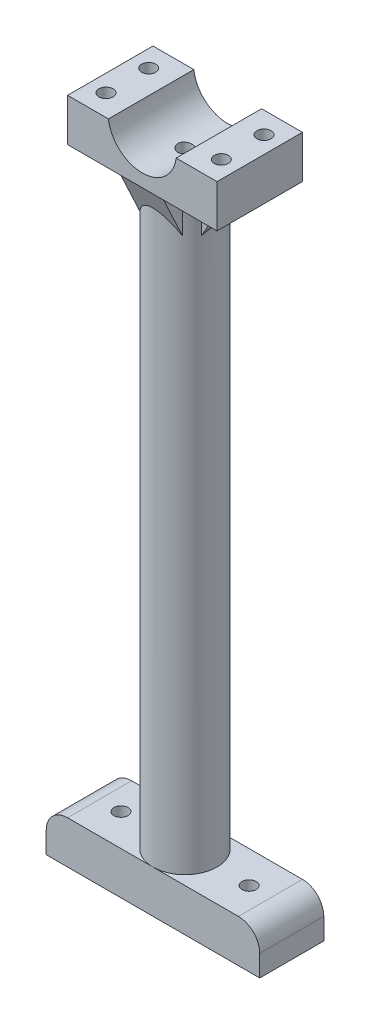
SolidWorks part; units mm, degrees
ref_plane "前视基准面" through (0, 0, 0) normal (0, 0, 1) x (1, 0, 0)
ref_plane "上视基准面" through (0, 0, 0) normal (0, 1, 0) x (1, 0, 0)
ref_plane "右视基准面" through (0, 0, 0) normal (1, 0, 0) x (0, 0, -1)
sketch "草图1" plane through (0, 0, 0) normal (0, 1, 0) x (1, 0, 0)
  line L1 (-25, -7.5) -> (25, -7.5)
  line L2 (-25, -7.5) -> (-25, 7.5)
  line L3 (-25, 7.5) -> (25, 7.5)
  line L4 (25, -7.5) -> (25, 7.5)
  line L5 (-25, -7.5) -> (25, 7.5) construction
  line L6 (-25, 7.5) -> (25, -7.5) construction
  point P0 (0, 0)
  dimension "D1" = 50
  dimension "D2" = 15
extrude "凸台-拉伸1" add sketch "草图1" along normal blind 10
sketch "草图2" plane through (0, 10, 0) normal (0, 1, 0) x (1, 0, 0)
  circle A0 centre (0, 0) radius 7.5
  dimension "D1" = 15
extrude "凸台-拉伸2" add sketch "草图2" along normal blind 150
sketch "草图3" plane through (0, 0, 0) normal (0, 0, 1) x (1, 0, 0)
  line L0 (-7.5, 160) -> (-7.5, 10) construction
  line L5 (0, 160) -> (0, 149)
  line L6 (-7.5, 160) -> (-7.5, 10) construction
  line L7 (7.5, 160) -> (-7.5, 160) construction
  line L8 (-17.5, 156) -> (17.5, 156)
  line L9 (-17.5, 156) -> (-17.5, 159)
  line L10 (-17.5, 159) -> (17.5, 159)
  line L11 (17.5, 156) -> (17.5, 159)
  line L12 (-17.5, 156) -> (17.5, 159) construction
  line L13 (-17.5, 159) -> (17.5, 156) construction
  line L14 (-17.5, 156) -> (-17.5, 149)
  line L15 (-17.5, 149) -> (17.5, 149)
  line L16 (17.5, 149) -> (17.5, 156)
  circle A0 centre (0, 160) radius 8
  circle A1 centre (0, 160) radius 11
  point P3 (0, 157.5)
  dimension "D1" = 16
  dimension "D2" = 22
  dimension "D3" = 10
  dimension "D4" = 1
  dimension "D5" = 7.5
  dimension "D6" = 0
  dimension "D7" = 3
extrude "凸台-拉伸3" add sketch "草图3" along normal blind 10 and the other way blind 10 contours A1 L10 L9 L8 | L10 A1 L8 A0 | L8 A1 L5 A0 | L5 A1 L8 A0 | L8 A1 L10 A0 | A1 L8 L11 L10 | A1 L8 L14 L15 | A1 L15 L16 L8
sketch "草图4" plane through (0, 0, 0) normal (0, 0, 1) x (1, 0, 0)
  line L1 (-15, 162.5) -> (15, 162.5)
  line L2 (-15, 162.5) -> (-15, 157.5)
  line L3 (-15, 157.5) -> (15, 157.5)
  line L4 (15, 162.5) -> (15, 157.5)
  line L5 (-15, 162.5) -> (15, 157.5) construction
  line L6 (-15, 157.5) -> (15, 162.5) construction
  line L8 (-15, 160) -> (15, 160)
  line L9 (-7.5, 149) -> (-7.5, 10) construction
  line L10 (7.5, 160) -> (-7.5, 160) construction
  circle A0 centre (0, 160) radius 8
  circle A1 centre (0, 160) radius 10
  dimension "D1" = 16
  dimension "D2" = 20
  dimension "D3" = 5
  dimension "D4" = 30
  dimension "D5" = 7.5
  dimension "D6" = 0
extrude "切除-拉伸2" cut sketch "草图4" against normal blind 100 and the other way blind 100 contours L8 A0 L3 | L3 A0
sketch "草图5" plane through (0, 0, 0) normal (0, -1, 0) x (1, 0, 0)
  circle A0 centre (0, 0) radius 1.65
  circle A1 centre (-15, 0) radius 1.65
  circle A2 centre (15, 0) radius 1.65
  dimension "D1" = 3.3
  dimension "D2" = 3.3
  dimension "D3" = 3.3
  dimension "D4" = 15
  dimension "D5" = 15
extrude "切除-拉伸3" cut sketch "草图5" against normal blind 10
sketch "草图6" plane through (0, 0, 0) normal (0, 0, 1) x (1, 0, 0)
  line L0 (0, 10) -> (0, 20)
  line L1 (-1.65, 10) -> (1.65, 10) construction
  line L2 (1.65, 10) -> (1.4, 15)
  line L3 (7.5, 10) -> (0, 10) construction
  line L4 (1.4, 15) -> (1.4, 20)
  line L5 (1.4, 20) -> (0, 20)
  line L6 (0, 10) -> (1.65, 10)
  dimension "D1" = 5
  dimension "D2" = 5
  dimension "D3" = 1.4
revolve "切除-旋转1" cut sketch "草图6" angle 360 about L0
sketch "草图7" plane through (0, 149, 0) normal (0, -1, 0) x (1, 0, 0)
  line L2 (-13.5, 5) -> (-13.5, -5)
  line L4 (13.5, 5) -> (13.5, -5)
  line L5 (-17.5, -10) -> (-17.5, 10) construction
  line L9 (17.5, -10) -> (17.5, 10) construction
  line L10 (-17.5, 10) -> (17.5, 10) construction
  line L11 (-17.5, -10) -> (17.5, -10) construction
  circle A0 centre (-13.5, 5) radius 1.65
  circle A1 centre (-13.5, -5) radius 1.65
  circle A2 centre (13.5, 5) radius 1.65
  circle A3 centre (13.5, -5) radius 1.65
  dimension "D1" = 3.3
  dimension "D2" = 3.3
  dimension "D3" = 3.3
  dimension "D4" = 3.3
  dimension "D5" = 4
  dimension "D6" = 4
  dimension "D7" = 5
  dimension "D8" = 5
  dimension "D9" = 5
  dimension "D10" = 5
  dimension "D11" = 10
fillet "圆角1" radius 5 2 edges at (-25, 10, 0) (25, 10, 0)
sketch "草图9" plane through (0, 0, 0) normal (0, 0, 1) x (1, 0, 0)
  line L1 (0, 152) -> (0, 153.4237)
  line L2 (0, 153.4237) -> (1.65, 153.4237)
  line L5 (1.4, 144.6198) -> (0, 144.6198)
  line L7 (0, 152) -> (0, 149)
  line L8 (-7.5, 149) -> (7.5, 149) construction
  line L9 (1.65, 153.4237) -> (1.65, 149)
  line L10 (1.65, 149) -> (1.4, 144.6198)
  line L11 (0, 149) -> (0, 144.6198)
  arc A0 (-7.9373, 159) -> (7.9373, 159) centre (0, 160) ccw construction
  dimension "D1" = 1.65
  dimension "D2" = 1.4
revolve "切除-旋转2" cut sketch "草图9" angle 360 about L7
extrude "切除-拉伸4" cut sketch "草图7" against normal blind 10
sketch "草图10" plane through (0, 0, 0) normal (0, 0, 1) x (1, 0, 0)
  line L0 (7.5, 149) -> (7.5, 140.3397)
  line L1 (7.5, 10) -> (7.5, 149) construction
  line L2 (7.5, 140.3397) -> (12.5, 149)
  line L3 (-17.5, 149) -> (17.5, 149) construction
  line L4 (12.5, 149) -> (7.5, 149)
  line L5 (-7.5, 149) -> (-7.5, 140.3397)
  line L6 (-7.5, 149) -> (-7.5, 10) construction
  line L7 (-7.5, 140.3397) -> (-12.5, 149)
  line L8 (-12.5, 149) -> (-7.5, 149)
  line L9 (-7.5, 149) -> (7.5, 149)
  line L10 (-7.5, 140.3397) -> (0, 127.3494)
  line L11 (0, 127.3494) -> (7.5, 140.3397)
  line L12 (0, 149) -> (0, 127.3494)
  dimension "D1" = 30
  dimension "D2" = 5
  dimension "D3" = 30
  dimension "D4" = 5
  dimension "D5" = 30
extrude "凸台-拉伸6" add sketch "草图10" along normal blind 3 and the other way blind 3 contours L8 L7 L5 | L12 L9 L5 L10 | L9 L12 L11 L0 | L2 L4 L0
sketch "草图11" plane through (0, 0, 0) normal (1, 0, 0) x (0, 0, -1)
  line L0 (-10, 149) -> (10, 149)
  line L1 (10, 149) -> (0, 127.5549)
  line L2 (0, 127.5549) -> (-10, 149)
  line L3 (0, 149) -> (0, 127.5549)
  dimension "D1" = 25
extrude "凸台-拉伸7" add sketch "草图11" along normal blind 5 and the other way blind 5 contours L3 L0 L2 | L0 L3 L1
